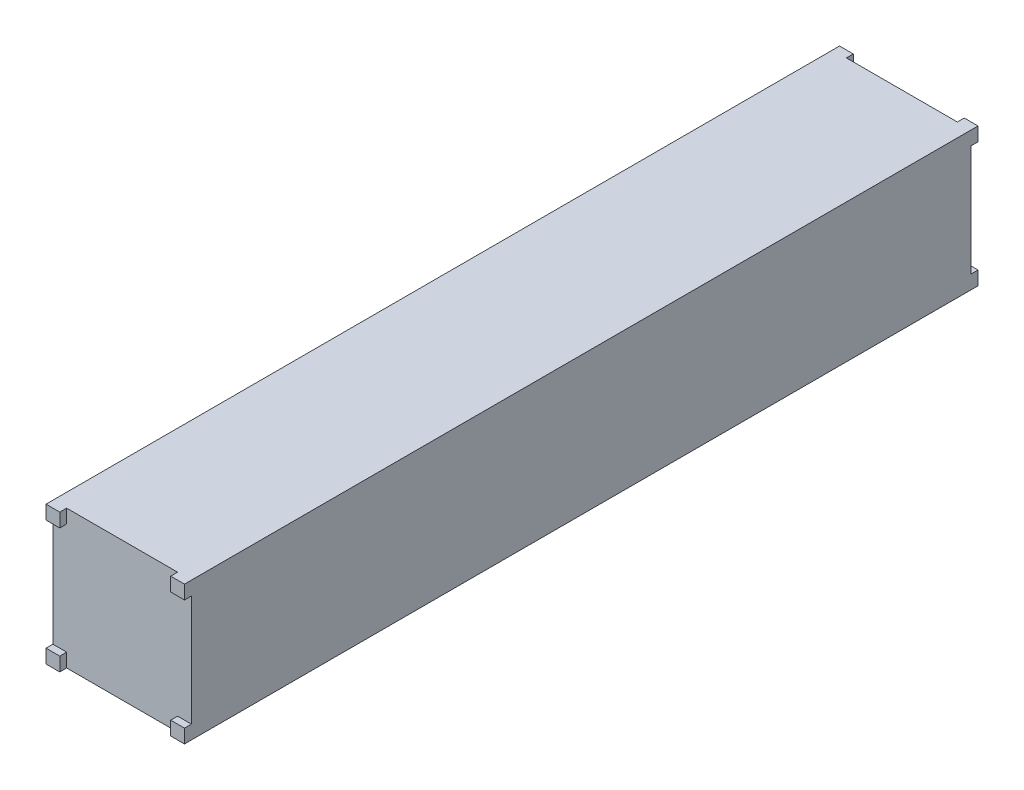
SolidWorks part; units mm, degrees
ref_plane "Front Plane" through (0, 0, 0) normal (0, 0, 1) x (1, 0, 0)
ref_plane "Top Plane" through (0, 0, 0) normal (0, 1, 0) x (1, 0, 0)
ref_plane "Right Plane" through (0, 0, 0) normal (1, 0, 0) x (0, 0, -1)
sketch "Sketch1" plane through (0, 0, 0) normal (0, 0, 1) x (1, 0, 0)
  line L1 (50.3, -50.3) -> (-50.3, -50.3)
  line L2 (50.3, -50.3) -> (50.3, 50.3)
  line L3 (50.3, 50.3) -> (-50.3, 50.3)
  line L4 (-50.3, -50.3) -> (-50.3, 50.3)
  line L5 (50.3, -50.3) -> (-50.3, 50.3) construction
  line L6 (50.3, 50.3) -> (-50.3, -50.3) construction
  point P0 (0, 0)
  dimension "D1" = 100.6
  dimension "D2" = 100.6
extrude "Boss-Extrude1" add sketch "Sketch1" along normal mid plane 566.5
sketch "Sketch2" plane through (0, 0, 283.25) normal (0, 0, 1) x (1, 0, 0)
  line L0 (0, 50.3) -> (0, -50.3) construction
  line L1 (-50.3, 50.3) -> (-40.3, 50.3)
  line L2 (-50.3, 50.3) -> (-50.3, 40.3)
  line L3 (-50.3, 40.3) -> (-40.3, 40.3)
  line L4 (-40.3, 50.3) -> (-40.3, 40.3)
  line L5 (50.3, 50.3) -> (-50.3, 50.3) construction
  line L6 (-50.3, -50.3) -> (50.3, -50.3) construction
  line L7 (50.3, 40.3) -> (40.3, 40.3)
  line L8 (40.3, 50.3) -> (40.3, 40.3)
  line L9 (50.3, 50.3) -> (40.3, 50.3)
  line L10 (50.3, 50.3) -> (50.3, 40.3)
  line L11 (-50.3, 0) -> (50.3, 0) construction
  line L12 (-50.3, 50.3) -> (-50.3, -50.3) construction
  line L13 (50.3, -50.3) -> (50.3, 50.3) construction
  line L14 (50.3, -50.3) -> (50.3, -40.3)
  line L15 (50.3, -50.3) -> (40.3, -50.3)
  line L16 (40.3, -50.3) -> (40.3, -40.3)
  line L17 (50.3, -40.3) -> (40.3, -40.3)
  line L18 (-50.3, -40.3) -> (-40.3, -40.3)
  line L19 (-40.3, -50.3) -> (-40.3, -40.3)
  line L20 (-50.3, -50.3) -> (-40.3, -50.3)
  line L21 (-50.3, -50.3) -> (-50.3, -40.3)
  dimension "D1" = 10
  dimension "D2" = 10
extrude "Boss-Extrude2" add sketch "Sketch2" along normal blind 5
sketch "Sketch3" plane through (0, 0, -283.25) normal (0, 0, -1) x (-1, 0, 0)
  line L0 (0, 50.3) -> (0, 0) construction
  line L1 (-50.3, 50.3) -> (-40.3, 50.3)
  line L2 (-50.3, 50.3) -> (-50.3, 40.3)
  line L3 (-50.3, 40.3) -> (-40.3, 40.3)
  line L4 (-40.3, 50.3) -> (-40.3, 40.3)
  line L5 (-50.3, 50.3) -> (50.3, 50.3) construction
  line L6 (0, 0) -> (50.3, 0) construction
  line L7 (50.3, 50.3) -> (50.3, -50.3) construction
  line L8 (50.3, 40.3) -> (40.3, 40.3)
  line L9 (40.3, 50.3) -> (40.3, 40.3)
  line L10 (50.3, 50.3) -> (40.3, 50.3)
  line L11 (50.3, 50.3) -> (50.3, 40.3)
  line L12 (50.3, -50.3) -> (50.3, -40.3)
  line L13 (50.3, -50.3) -> (40.3, -50.3)
  line L14 (40.3, -50.3) -> (40.3, -40.3)
  line L15 (50.3, -40.3) -> (40.3, -40.3)
  line L16 (-50.3, -40.3) -> (-40.3, -40.3)
  line L17 (-40.3, -50.3) -> (-40.3, -40.3)
  line L18 (-50.3, -50.3) -> (-40.3, -50.3)
  line L19 (-50.3, -50.3) -> (-50.3, -40.3)
  dimension "D1" = 10
  dimension "D2" = 10
extrude "Boss-Extrude3" add sketch "Sketch3" along normal blind 5
